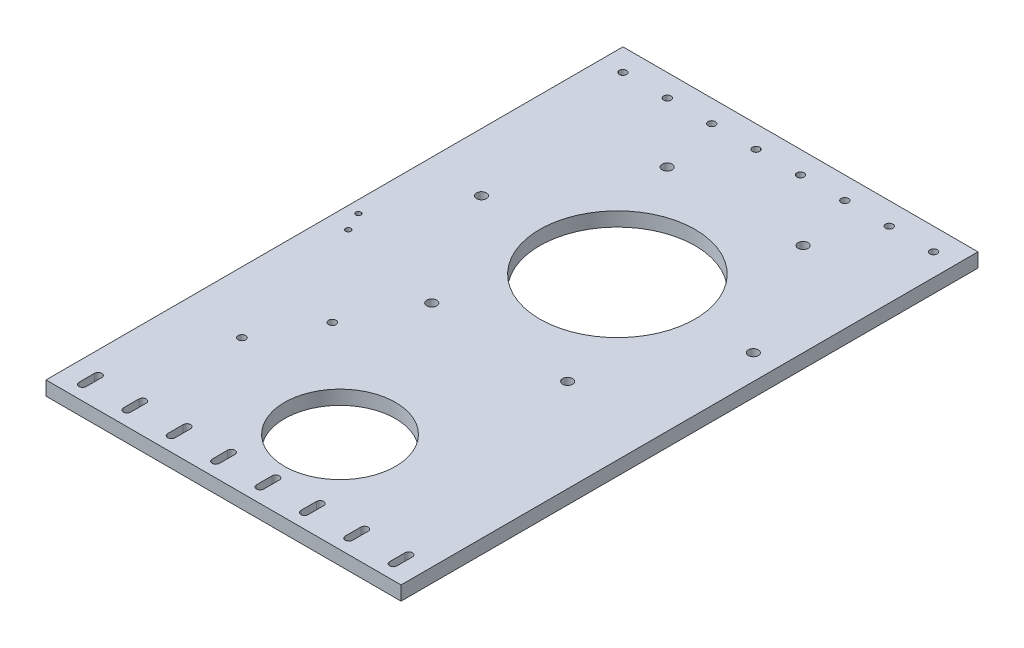
SolidWorks part; units mm, degrees
material "6061 Alloy"
ref_plane "Front Plane" through (0, 0, 0) normal (0, 0, 1) x (1, 0, 0)
ref_plane "Top Plane" through (0, 0, 0) normal (0, 1, 0) x (1, 0, 0)
ref_plane "Right Plane" through (0, 0, 0) normal (1, 0, 0) x (0, 0, -1)
sketch "Sketch1" plane through (0, 0, 0) normal (0, 1, 0) x (1, 0, 0)
  line L0 (87.5, 260) -> (87.5, 0) construction
  line L1 (0, 0) -> (160, 0)
  line L2 (0, 0) -> (0, 260)
  line L3 (0, 260) -> (160, 260)
  line L4 (160, 0) -> (160, 260)
  line L5 (87.5, 170) -> (148.75, 170) construction
  line L6 (10, 6.5) -> (10, 13.5) construction
  line L7 (5.4755, 135.2989) -> (9.5163, 126.7011) construction
  line L8 (22, 0) -> (22, 260) construction
  line L9 (22, 136) -> (0, 136) construction
  line L10 (22, 126) -> (0, 126) construction
  line L11 (0, 136) -> (0, 126) construction
  line L12 (17.3003, 136) -> (22, 126) construction
  line L13 (8.35, 6.5) -> (8.35, 13.5)
  line L14 (11.65, 6.5) -> (11.65, 13.5)
  line L15 (10, 250) -> (10, 0) construction
  line L16 (31.65, 6.5) -> (31.65, 13.5)
  line L17 (28.35, 6.5) -> (28.35, 13.5)
  line L18 (30, 6.5) -> (30, 13.5) construction
  line L19 (51.65, 6.5) -> (51.65, 13.5)
  line L20 (48.35, 6.5) -> (48.35, 13.5)
  line L21 (50, 6.5) -> (50, 13.5) construction
  line L22 (71.65, 6.5) -> (71.65, 13.5)
  line L23 (68.35, 6.5) -> (68.35, 13.5)
  line L24 (70, 6.5) -> (70, 13.5) construction
  line L25 (91.65, 6.5) -> (91.65, 13.5)
  line L26 (88.35, 6.5) -> (88.35, 13.5)
  line L27 (90, 6.5) -> (90, 13.5) construction
  line L28 (111.65, 6.5) -> (111.65, 13.5)
  line L29 (108.35, 6.5) -> (108.35, 13.5)
  line L30 (110, 6.5) -> (110, 13.5) construction
  line L31 (131.65, 6.5) -> (131.65, 13.5)
  line L32 (128.35, 6.5) -> (128.35, 13.5)
  line L33 (130, 6.5) -> (130, 13.5) construction
  line L34 (151.65, 6.5) -> (151.65, 13.5)
  line L35 (148.35, 6.5) -> (148.35, 13.5)
  line L36 (150, 6.5) -> (150, 13.5) construction
  line L37 (10, 250) -> (30, 250) construction
  circle A0 centre (87.5, 170) radius 35
  circle A1 centre (87.5, 45) radius 25
  circle A2 centre (87.5, 170) radius 61.25 construction
  circle A3 centre (148.75, 170) radius 2.25
  circle A4 centre (118.125, 116.9559) radius 2.25
  circle A5 centre (56.875, 116.9559) radius 2.25
  circle A6 centre (26.25, 170) radius 2.25
  circle A7 centre (56.875, 223.0441) radius 2.25
  circle A8 centre (118.125, 223.0441) radius 2.25
  circle A10 centre (5.4755, 135.2989) radius 1.175
  circle A11 centre (9.5163, 126.7011) radius 1.175
  circle A12 centre (87.5, 170) radius 78 construction
  circle A13 centre (10, 250) radius 1.65
  arc A14 (8.35, 6.5) -> (11.65, 6.5) centre (10, 6.5) ccw
  arc A15 (11.65, 13.5) -> (8.35, 13.5) centre (10, 13.5) ccw
  circle A16 centre (30, 250) radius 1.65
  arc A17 (28.35, 6.5) -> (31.65, 6.5) centre (30, 6.5) ccw
  arc A18 (31.65, 13.5) -> (28.35, 13.5) centre (30, 13.5) ccw
  circle A19 centre (50, 250) radius 1.65
  arc A20 (48.35, 6.5) -> (51.65, 6.5) centre (50, 6.5) ccw
  arc A21 (51.65, 13.5) -> (48.35, 13.5) centre (50, 13.5) ccw
  circle A22 centre (70, 250) radius 1.65
  arc A23 (68.35, 6.5) -> (71.65, 6.5) centre (70, 6.5) ccw
  arc A24 (71.65, 13.5) -> (68.35, 13.5) centre (70, 13.5) ccw
  circle A25 centre (90, 250) radius 1.65
  arc A26 (88.35, 6.5) -> (91.65, 6.5) centre (90, 6.5) ccw
  arc A27 (91.65, 13.5) -> (88.35, 13.5) centre (90, 13.5) ccw
  circle A28 centre (110, 250) radius 1.65
  arc A29 (108.35, 6.5) -> (111.65, 6.5) centre (110, 6.5) ccw
  arc A30 (111.65, 13.5) -> (108.35, 13.5) centre (110, 13.5) ccw
  circle A31 centre (130, 250) radius 1.65
  arc A32 (128.35, 6.5) -> (131.65, 6.5) centre (130, 6.5) ccw
  arc A33 (131.65, 13.5) -> (128.35, 13.5) centre (130, 13.5) ccw
  circle A34 centre (150, 250) radius 1.65
  arc A35 (148.35, 6.5) -> (151.65, 6.5) centre (150, 6.5) ccw
  arc A36 (151.65, 13.5) -> (148.35, 13.5) centre (150, 13.5) ccw
  point P15 (87.5, 170)
  point P29 (10, 10)
  point P42 (7.4959, 131)
  point P43 (0, 131)
  point P55 (30, 10)
  point P65 (50, 10)
  point P74 (70, 10)
  point P83 (90, 10)
  point P92 (110, 10)
  point P101 (130, 10)
  point P110 (150, 10)
  dimension "D3" = 70
  dimension "D4" = 50
  dimension "D7" = 122.5
  dimension "D8" = 4.5
  dimension "D11" = 124
  dimension "D13" = 2.35
  dimension "D16" = 156
  dimension "D19" = 3.3
  dimension "D24" = 240
  dimension "D1" = 160
  dimension "D2" = 260
  dimension "D5" = 125
  dimension "D6" = 90
  dimension "D10" = 61.25
  dimension "D12" = 65.5
  dimension "D14" = 9.5
  dimension "D15" = 10
  dimension "D17" = 11
  dimension "D18" = 72.5
  dimension "D20" = 10
  dimension "D21" = 10
  dimension "D22" = 3.3
  dimension "D23" = 7
  dimension "D26" = 20
  dimension "D25" = 8
  dimension "D9" = 6
extrude "Boss-Extrude1" add sketch "Sketch1" along normal blind 6.35 contours A1 | A0 | A4 | A8 | A7 | A6 | L4 L3 L2 L1 | A3 | A5 | A11 | A10 | A28 | A25 | A31 | A34 | A22 | A19 | A16 | A13 | L14 A15 L13 A14 | L16 A18 L17 A17 | L19 A21 L20 A20 | L22 A24 L23 A23 | L25 A27 L26 A26 | L28 A30 L29 A29 | L31 A33 L32 A32 | L34 A36 L35 A35
sketch "Sketch2" plane through (0, 6.35, 0) normal (0, 1, 0) x (1, 0, 0)
  line L0 (27.6639, 60.641) -> (42.0639, 86.959) construction
  line L1 (87.5, 170) -> (42.0639, 86.959) construction
  line L2 (34.8639, 73.8) -> (87.5, 45) construction
  circle A0 centre (27.6639, 60.641) radius 1.7
  circle A1 centre (42.0639, 86.959) radius 1.7
  point P7 (26.8777, 92.2951)
  dimension "D1" = 3.4
  dimension "D2" = 30
  dimension "D3" = 60
extrude "Cut-Extrude1" cut sketch "Sketch2" against normal through all
